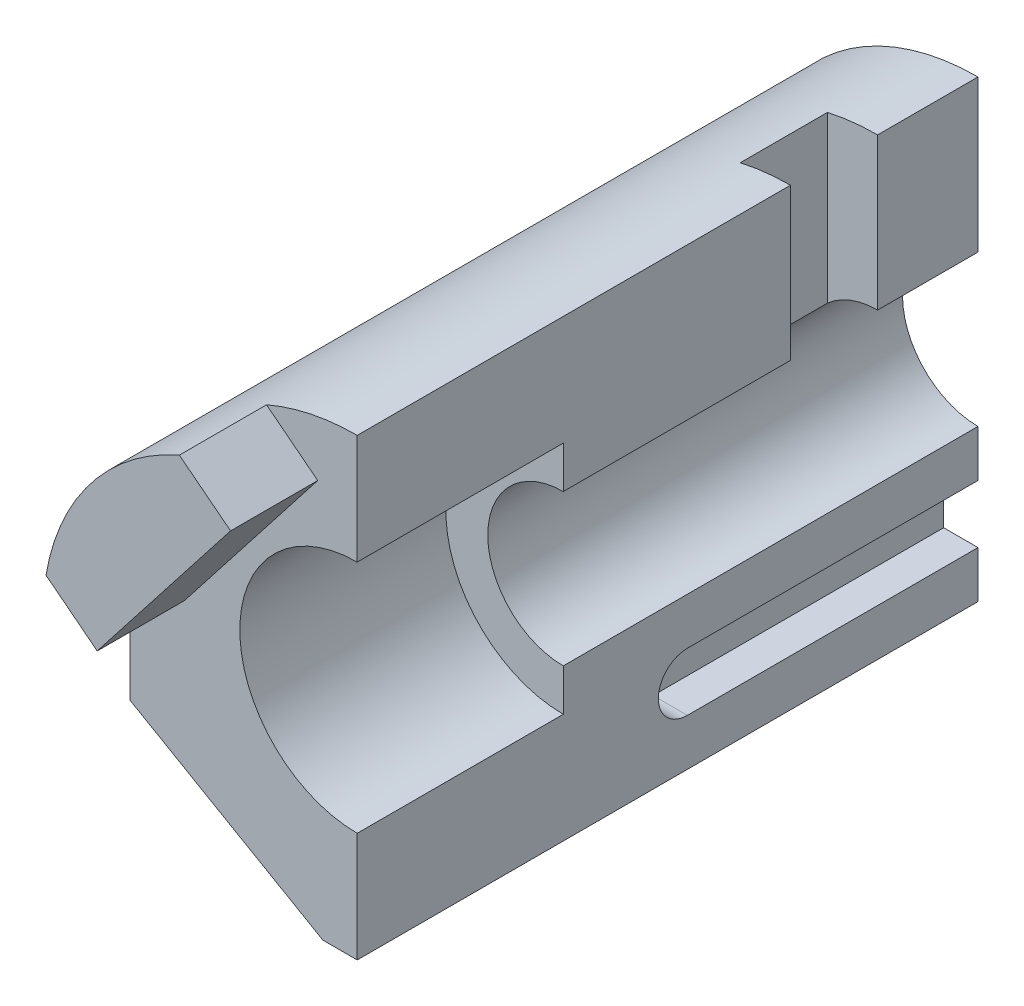
SolidWorks part; units mm, degrees
material "Alliage 1060"
ref_plane "Plan de face" through (0, 0, 0) normal (0, 0, 1) x (1, 0, 0)
ref_plane "Plan de dessus" through (0, 0, 0) normal (0, 1, 0) x (1, 0, 0)
ref_plane "Plan de droite" through (0, 0, 0) normal (1, 0, 0) x (0, 0, -1)
sketch "Esquisse1" plane through (0, 0, 0) normal (0, 0, 1) x (1, 0, 0)
  line L0 (0, 0) -> (-13, 0)
  line L1 (-13, 0) -> (-86, 42.1466)
  line L2 (-86, 42.1466) -> (-86, 85.9991)
  line L3 (0, 172) -> (0, 0)
  arc A1 (-86, 85.9991) -> (0, 172) centre (0, 86) cw
  point P7 (-87.0039, 76.3204)
  point P8 (-86.9313, 76.2498)
  point P9 (0, 0)
  point P10 (0, 0)
  point P11 (-87.614, 82.8766)
  point P12 (-86, 86)
  point P13 (0, 0)
  point P14 (0, 0)
  dimension "D5" = 86
  dimension "D1" = 86
  dimension "D2" = 13
  dimension "D3" = 86
  dimension "D4" = 30
extrude "Boss.-Extru.2" add sketch "Esquisse1" along normal blind 235
sketch "Esquisse2" plane through (0, 0, 235) normal (0, 0, 1) x (1, 0, 0)
  line L0 (0, 0) -> (0, 172) construction
  circle A0 centre (0, 86) radius 44.45
extrude "Enlèv. mat.-Extru.1" cut sketch "Esquisse2" against normal blind 78
sketch "Esquisse3" plane through (0, 0, 157) normal (0, 0, 1) x (1, 0, 0)
  line L0 (0, 41.55) -> (0, 130.45) construction
  circle A0 centre (0, 86) radius 28.575
extrude "Enlèv. mat.-Extru.2" cut sketch "Esquisse3" against normal blind 190
sketch "Esquisse4" plane through (0, 0, 0) normal (1, 0, 0) x (0, 0, -1)
  line L0 (0, 28.7125) -> (-110, 28.7125) construction
  line L1 (0, 0) -> (0, 57.425) construction
  line L2 (0, 17.7125) -> (-110, 17.7125)
  line L3 (0, 39.7125) -> (-110, 39.7125)
  arc A0 (0, 17.7125) -> (0, 39.7125) centre (0, 28.7125) ccw
  arc A1 (-110, 39.7125) -> (-110, 17.7125) centre (-110, 28.7125) ccw
  point P4 (-55, 28.7125)
  dimension "D1" = 110
extrude "Enlèv. mat.-Extru.3" cut sketch "Esquisse4" against normal blind 13
sketch "Esquisse7" plane through (0, 0, 157) normal (0, 0, 1) x (1, 0, 0)
  line L0 (0, 86) -> (-121.0908, 180.6065) construction
  line L1 (-34.3296, 164.851) -> (-14.9464, 149.7072)
  line L2 (-14.9464, 149.7072) -> (-40.1885, 117.3987)
  line L3 (-40.1885, 117.3987) -> (-65.4307, 85.0903)
  line L4 (-65.4307, 85.0903) -> (-84.8139, 100.2341)
  line L5 (-13, 0) -> (0, 0) construction
  arc A0 (0, 172) -> (-86, 85.9991) centre (0, 86) ccw construction
  arc A1 (-34.3296, 164.851) -> (-84.8139, 100.2341) centre (0, 86) ccw
  point P8 (0, 0)
  point P12 (0, 0)
  dimension "D1" = 41
  dimension "D2" = 41
  dimension "D3" = 51
  dimension "D4" = 38
  dimension "D5" = 38
  dimension "D6" = 13
extrude "Boss.-Extru.3" add sketch "Esquisse7" along normal blind 111 contours L1 L2 L3 L4 A1
sketch "Esquisse10" plane through (0, 0, 0) normal (1, 0, 0) x (0, 0, -1)
  line L0 (-235, 172) -> (0, 172) construction
  line L1 (-71, 172) -> (-38, 172)
  line L2 (-71, 172) -> (-71, 132.4506)
  line L3 (-71, 132.4506) -> (-38, 132.4506)
  line L4 (-38, 172) -> (-38, 132.4506)
  dimension "D1" = 38
  dimension "D2" = 33
extrude "Enlèv. mat.-Extru.5" cut sketch "Esquisse10" against normal blind 19
sketch "Esquisse11" plane through (0, 132.4506, 0) normal (0, 1, 0) x (1, 0, 0)
  line L3 (-19, -71) -> (0, -71)
  line L4 (-19, -71) -> (-19, -38)
  line L5 (-19, -38) -> (0, -38)
  line L6 (0, -71) -> (0, -38)
extrude "Enlèv. mat.-Extru.6" cut sketch "Esquisse11" against normal up to next
equation "\"A\"= 235"
equation "\"B\"= 110"
equation "\"c\"= 86"
equation "\"D5@Esquisse1\"=\"c\""
equation "\"D1@Esquisse1\"=\"c\""
equation "\"D3@Esquisse1\"=\"c\""
equation "\"D1@Boss.-Extru.2\"=\"A\""
equation "\"D1@Esquisse4\"=\"B\""
